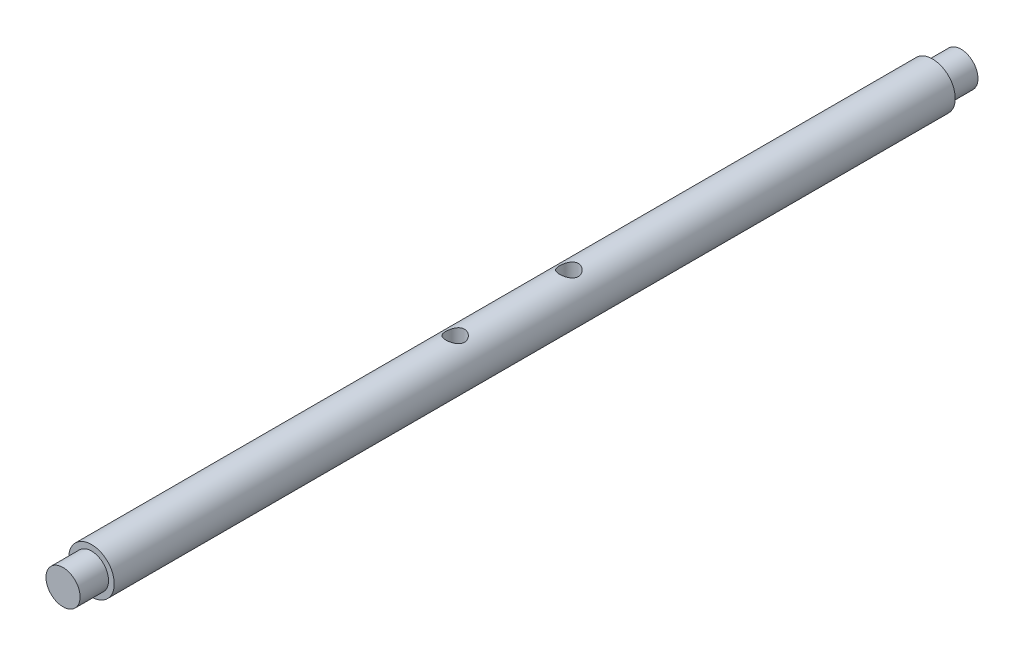
SolidWorks part; units mm, degrees
material "5052-H34"
ref_plane "正面" through (0, 0, 0) normal (0, 0, 1) x (1, 0, 0)
ref_plane "平面" through (0, 0, 0) normal (0, 1, 0) x (1, 0, 0)
ref_plane "右側面" through (0, 0, 0) normal (1, 0, 0) x (0, 0, -1)
sketch "ｽｹｯﾁ1" plane through (0, 0, 0) normal (0, 0, 1) x (1, 0, 0)
  circle A0 centre (0, 0) radius 4
  dimension "D1" = 8
extrude "ﾎﾞｽ - 押し出し1" add sketch "ｽｹｯﾁ1" along normal blind 147.8
sketch "ｽｹｯﾁ2" plane through (0, 0, 147.8) normal (0, 0, 1) x (1, 0, 0)
  circle A0 centre (0, 0) radius 3
  dimension "D1" = 6
extrude "ﾎﾞｽ - 押し出し2" add sketch "ｽｹｯﾁ2" along normal blind 5
ref_plane "平面1" through (0, 0, 73.9) normal (0, 0, 1) x (1, 0, 0)
mirror "ﾐﾗｰ1" about plane through (0, 0, 73.9) normal (0, 0, 1) of "ﾎﾞｽ - 押し出し2"
sketch "ｽｹｯﾁ3" plane through (0, 0, 0) normal (0, 1, 0) x (1, 0, 0)
  line L0 (0, 5) -> (0, -152.8) construction
  line L3 (3, 5) -> (-3, 5) construction
  line L4 (-3, -152.8) -> (3, -152.8) construction
  line L5 (4, -73.9) -> (-4, -73.9) construction
  line L6 (4, -147.8) -> (4, 0) construction
  line L7 (-4, 0) -> (-4, -147.8) construction
  circle A0 centre (0, -63.9) radius 1.65
  circle A1 centre (0, -83.9) radius 1.65
  dimension "D1" = 3.3
  dimension "D2" = 20
extrude "ｶｯﾄ - 押し出し1" cut sketch "ｽｹｯﾁ3" against normal through all both and the other way through all
